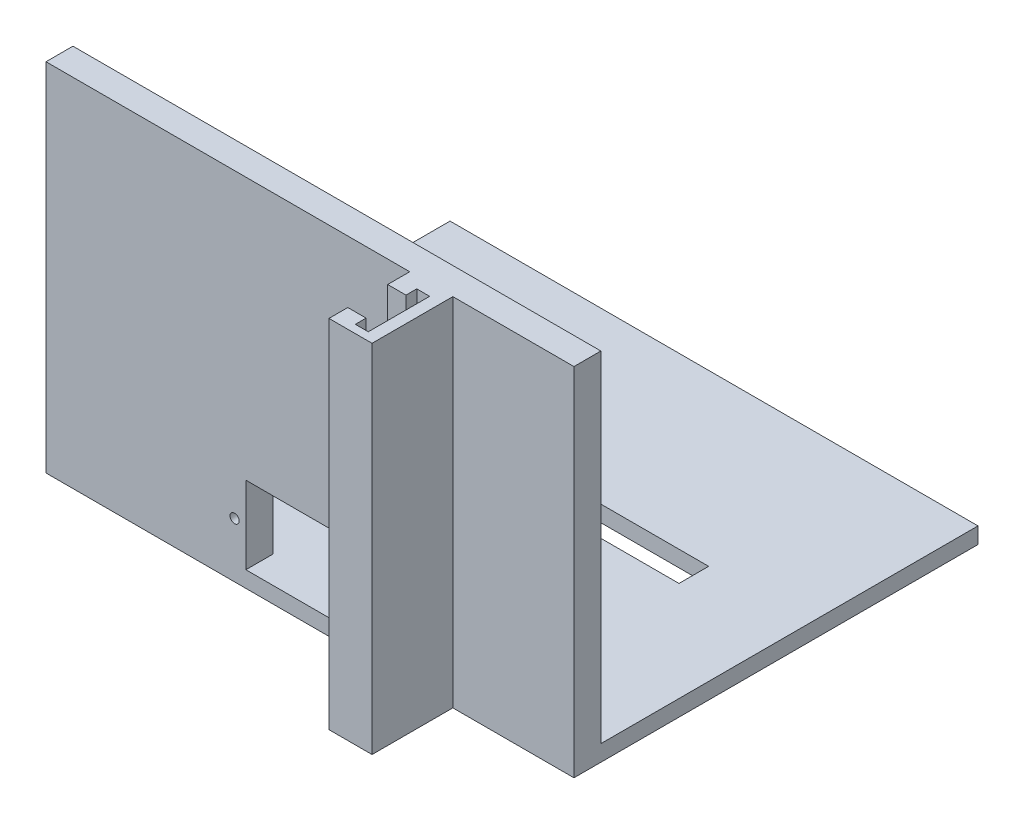
SolidWorks part; units mm, degrees
ref_plane "Front Plane" through (0, 0, 0) normal (0, 0, 1) x (1, 0, 0)
ref_plane "Top Plane" through (0, 0, 0) normal (0, 1, 0) x (1, 0, 0)
ref_plane "Right Plane" through (0, 0, 0) normal (1, 0, 0) x (0, 0, -1)
sketch "Sketch1" plane through (0, 0, 0) normal (0, 0, 1) x (1, 0, 0)
  line L0 (-11.9, 7.2) -> (11.9, 7.2)
  line L1 (-49, 55.9146) -> (49, 55.9146)
  line L2 (-49, 55.9146) -> (-49, -55.9146)
  line L3 (-49, -55.9146) -> (49, -55.9146)
  line L4 (49, 55.9146) -> (49, -55.9146)
  line L5 (-49, 55.9146) -> (49, -55.9146) construction
  line L6 (-49, -55.9146) -> (49, 55.9146) construction
  line L7 (-11.9, 7.2) -> (-11.9, -7.2)
  line L8 (-11.9, -7.2) -> (11.9, -7.2)
  line L9 (11.9, 7.2) -> (11.9, -7.2)
  line L10 (-11.9, 7.2) -> (11.9, -7.2) construction
  line L11 (-11.9, -7.2) -> (11.9, 7.2) construction
  circle A0 centre (14, 0) radius 0.85
  circle A1 centre (-14, 0) radius 0.85
  point P0 (0, 0)
  point P6 (0, 0)
  dimension "D5" = 1.7
  dimension "D6" = 98
  dimension "D1" = 23.8
  dimension "D2" = 14.4
  dimension "D3" = 14
  dimension "D4" = 14
extrude "Boss-Extrude1" add sketch "Sketch1" along normal blind 5
sketch "Sketch3" plane through (0, 0, 0) normal (0, 0, -1) x (-1, 0, 0)
  line L0 (49, 55.9146) -> (49, -55.9146) construction
  line L1 (-49, -10.2) -> (49, -10.2)
  line L2 (-49, -10.2) -> (-49, -7.2)
  line L3 (-49, -7.2) -> (49, -7.2)
  line L4 (49, -10.2) -> (49, -7.2)
  line L5 (-49, -10.2) -> (49, -7.2) construction
  line L6 (-49, -7.2) -> (49, -10.2) construction
  line L7 (11.9, -7.2) -> (-11.9, -7.2) construction
  line L8 (-49, -55.9146) -> (-49, 55.9146) construction
  point P0 (0, -8.7)
  dimension "D1" = 3
extrude "Boss-Extrude2" add sketch "Sketch3" along normal blind 70
sketch "Sketch4" plane through (0, -7.2, 0) normal (0, 1, 0) x (1, 0, 0)
  line L0 (49, 0) -> (-49, 0) construction
  line L1 (30.5, 33) -> (-30.5, 33)
  line L2 (30.5, 33) -> (30.5, 38.5)
  line L3 (30.5, 38.5) -> (-30.5, 38.5)
  line L4 (-30.5, 33) -> (-30.5, 38.5)
  line L5 (30.5, 33) -> (-30.5, 38.5) construction
  line L6 (30.5, 38.5) -> (-30.5, 33) construction
  point P0 (0, 35.75)
  dimension "D1" = 5.5
  dimension "D2" = 61
  dimension "D3" = 33
extrude "Cut-Extrude1" cut sketch "Sketch4" against normal blind 50
sketch "Sketch5" plane through (0, 0, 0) normal (0, 0, -1) x (-1, 0, 0)
  line L4 (49, -10.2) -> (-49, -10.2)
  line L5 (-49, -10.2) -> (-49, -55.9146)
  line L6 (-49, -55.9146) -> (49, -55.9146)
  line L7 (49, -55.9146) -> (49, -10.2)
  line L8 (49, -10.2) -> (-49, -10.2)
  line L9 (-49, -10.2) -> (-49, -55.9146)
  line L10 (-49, -55.9146) -> (49, -55.9146)
  line L11 (49, -55.9146) -> (49, -10.2)
  dimension "D1" = 0
extrude "Cut-Extrude2" cut sketch "Sketch5" against normal through all both and the other way through all
sketch "Sketch6" plane through (0, 0, 5) normal (0, 0, 1) x (1, 0, 0)
  line L1 (18.52, 55.9146) -> (26.52, 55.9146)
  line L2 (18.52, 55.9146) -> (18.52, -4.0854)
  line L3 (18.52, -4.0854) -> (26.52, -4.0854)
  line L4 (26.52, 55.9146) -> (26.52, -4.0854)
  line L5 (18.52, 55.9146) -> (26.52, -4.0854) construction
  line L6 (18.52, -4.0854) -> (26.52, 55.9146) construction
  line L7 (11.9, -7.2) -> (11.9, 7.2) construction
  line L8 (49, 55.9146) -> (-49, 55.9146) construction
  point P0 (22.52, 25.9146)
  dimension "D1" = 14.62
  dimension "D2" = 8
  dimension "D3" = 60
extrude "Boss-Extrude3" add sketch "Sketch6" along normal blind 15
sketch "Sketch7" plane through (0, 55.9146, 0) normal (0, 1, 0) x (1, 0, 0)
  line L0 (18.52, -9.1) -> (21.92, -9.1)
  line L1 (18.52, -20) -> (18.52, -5) construction
  line L2 (21.92, -9.1) -> (21.92, -7.1)
  line L3 (21.92, -7.1) -> (24.32, -7.1)
  line L4 (24.32, -7.1) -> (24.32, -18.5)
  line L5 (24.32, -18.5) -> (21.92, -18.5)
  line L6 (21.92, -18.5) -> (21.92, -16.5)
  line L7 (21.92, -16.5) -> (18.52, -16.5)
  line L8 (26.52, -20) -> (18.52, -20) construction
  line L9 (18.52, -9.1) -> (18.52, -16.5)
  dimension "D1" = 7.4
  dimension "D2" = 11.4
  dimension "D3" = 2.4
  dimension "D4" = 3.4
  dimension "D5" = 3.5
extrude "Cut-Extrude3" cut sketch "Sketch7" against normal through all
sketch "Sketch8" plane through (0, -4.0854, 0) normal (0, -1, 0) x (1, 0, 0)
  line L12 (21.92, 7.1) -> (21.92, 9.1)
  line L13 (21.92, 9.1) -> (18.52, 9.1)
  line L14 (18.52, 9.1) -> (18.52, 5)
  line L15 (18.52, 5) -> (26.52, 5)
  line L16 (26.52, 5) -> (26.52, 20)
  line L17 (26.52, 20) -> (18.52, 20)
  line L18 (18.52, 20) -> (18.52, 16.5)
  line L19 (18.52, 16.5) -> (21.92, 16.5)
  line L20 (21.92, 16.5) -> (21.92, 18.5)
  line L21 (21.92, 18.5) -> (24.32, 18.5)
  line L22 (24.32, 18.5) -> (24.32, 7.1)
  line L23 (24.32, 7.1) -> (21.92, 7.1)
  line L24 (21.92, 7.1) -> (21.92, 9.1)
  line L25 (21.92, 9.1) -> (18.52, 9.1)
  line L26 (18.52, 9.1) -> (18.52, 5)
  line L27 (18.52, 5) -> (26.52, 5)
  line L28 (26.52, 5) -> (26.52, 20)
  line L29 (26.52, 20) -> (18.52, 20)
  line L30 (18.52, 20) -> (18.52, 16.5)
  line L31 (18.52, 16.5) -> (21.92, 16.5)
  line L32 (21.92, 16.5) -> (21.92, 18.5)
  line L33 (21.92, 18.5) -> (24.32, 18.5)
  line L34 (24.32, 18.5) -> (24.32, 7.1)
  line L35 (24.32, 7.1) -> (21.92, 7.1)
  dimension "D1" = 0
extrude "Boss-Extrude4" add sketch "Sketch8" along normal up to surface (6.1146 mm away) up to face at (0, -10.2, -35.75)
